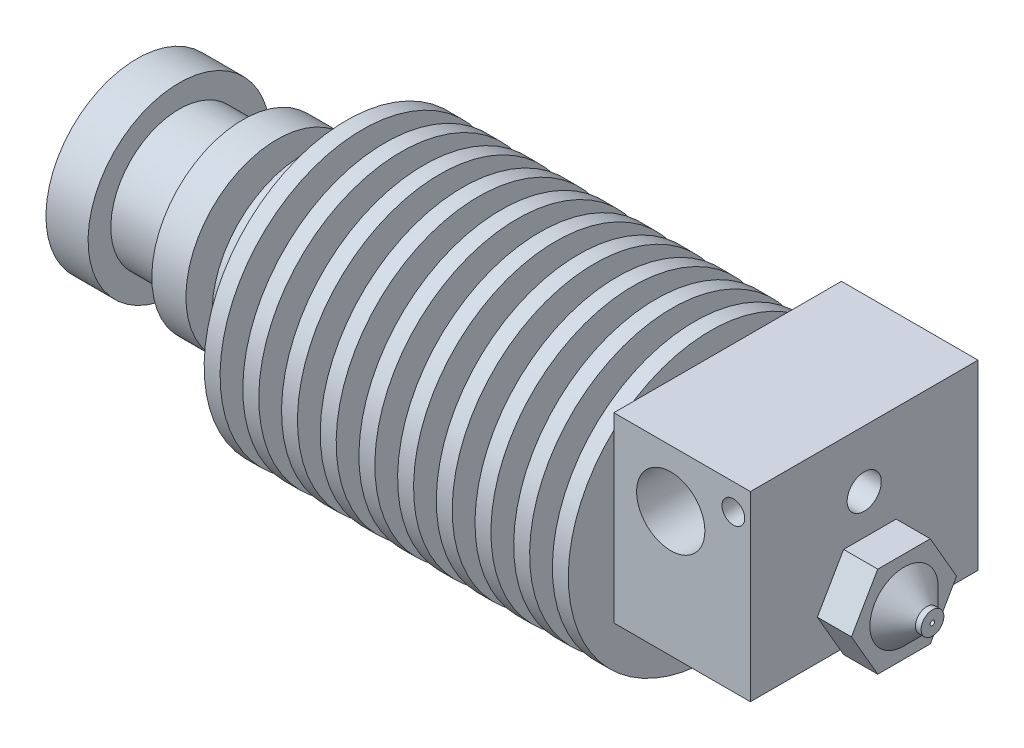
SolidWorks part; units mm, degrees
ref_plane "Front Plane" through (0, 0, 0) normal (0, 0, 1) x (1, 0, 0)
ref_plane "Top Plane" through (0, 0, 0) normal (0, 1, 0) x (1, 0, 0)
ref_plane "Right Plane" through (0, 0, 0) normal (1, 0, 0) x (0, 0, -1)
sketch "Sketch1" plane through (0, 0, 0) normal (0, 0, 1) x (1, 0, 0)
  line L0 (0, 0) -> (69.9, 0) construction
  line L1 (0, -8) -> (0, 8) construction
  line L2 (0, 8) -> (3.7, 8)
  line L3 (3.7, 8) -> (3.7, 6)
  line L4 (3.7, 6) -> (9.3, 6)
  line L5 (9.3, 6) -> (9.3, 8)
  line L6 (9.3, 8) -> (12.3, 8)
  line L7 (12.3, 8) -> (12.3, 3.75)
  line L8 (12.3, 3.75) -> (14.6, 3.75)
  line L9 (14.6, 3.75) -> (14.6, 8)
  line L10 (14.6, 8) -> (16.6, 8)
  line L11 (16.6, 8) -> (16.6, 3.75)
  line L12 (16.6, 3.75) -> (18.4, 3.75)
  line L13 (18.4, 3.75) -> (18.4, 12.5)
  line L14 (18.4, 12.5) -> (50.4, 12.5) construction
  line L15 (50.4, 12.5) -> (50.4, 3)
  line L16 (50.4, 3) -> (64.4, 3)
  line L17 (64.4, 3) -> (64.4, 4)
  line L18 (64.4, 4) -> (67.4, 4)
  line L19 (67.4, 3) -> (69.4, 1)
  line L20 (69.4, 1) -> (69.9, 1)
  line L21 (69.9, 1) -> (69.9, -1) construction
  line L23 (50.4, -12.5) -> (50.4, -3) construction
  line L24 (18.4, -12.5) -> (50.4, -12.5) construction
  line L25 (18.4, -3.75) -> (18.4, -12.5) construction
  line L26 (16.6, -3.75) -> (18.4, -3.75) construction
  line L27 (16.6, -8) -> (16.6, -3.75) construction
  line L28 (14.6, -8) -> (16.6, -8) construction
  line L29 (14.6, -3.75) -> (14.6, -8) construction
  line L30 (12.3, -3.75) -> (14.6, -3.75) construction
  line L31 (12.3, -8) -> (12.3, -3.75) construction
  line L32 (9.3, -8) -> (12.3, -8) construction
  line L33 (9.3, -6) -> (9.3, -8) construction
  line L34 (3.7, -6) -> (9.3, -6) construction
  line L35 (3.7, -8) -> (3.7, -6) construction
  line L36 (0, -8) -> (3.7, -8) construction
  line L37 (69.4, -1) -> (69.9, -1) construction
  line L38 (67.4, -3) -> (69.4, -1) construction
  line L39 (64.4, -4) -> (67.4, -4) construction
  line L40 (64.4, -3) -> (64.4, -4) construction
  line L41 (50.4, -3) -> (64.4, -3) construction
  line L42 (0, 4.75) -> (0, 8)
  line L43 (69.9, 0.2) -> (69.9, 1)
  line L44 (67.4, 3) -> (67.4, -3) construction
  line L45 (67.4, 3) -> (67.4, 4)
  line L46 (67.4, -3) -> (67.4, -4) construction
  line L47 (18.4, 12.5) -> (19.8, 12.5)
  line L48 (19.8, 12.5) -> (19.8, 3.75)
  line L49 (19.8, 3.75) -> (21.8, 3.75)
  line L50 (21.8, 3.75) -> (21.8, 12.5)
  line L51 (21.8, 12.5) -> (23.2, 12.5)
  line L52 (23.2, 12.5) -> (23.2, 3.75)
  line L53 (23.2, 3.75) -> (25.2, 3.75)
  line L54 (25.2, 3.75) -> (25.2, 12.5)
  line L55 (25.2, 12.5) -> (26.6, 12.5)
  line L56 (26.6, 12.5) -> (26.6, 3.75)
  line L57 (26.6, 3.75) -> (28.6, 3.75)
  line L58 (28.6, 3.75) -> (28.6, 12.5)
  line L59 (28.6, 12.5) -> (30, 12.5)
  line L60 (30, 12.5) -> (30, 3.75)
  line L61 (30, 3.75) -> (32, 3.75)
  line L62 (32, 3.75) -> (32, 12.5)
  line L63 (32, 12.5) -> (33.4, 12.5)
  line L64 (33.4, 12.5) -> (33.4, 3.75)
  line L65 (33.4, 3.75) -> (35.4, 3.75)
  line L66 (35.4, 3.75) -> (35.4, 12.5)
  line L67 (35.4, 12.5) -> (36.8, 12.5)
  line L68 (36.8, 12.5) -> (36.8, 3.75)
  line L69 (36.8, 3.75) -> (38.8, 3.75)
  line L70 (38.8, 3.75) -> (38.8, 12.5)
  line L71 (38.8, 12.5) -> (40.2, 12.5)
  line L72 (40.2, 12.5) -> (40.2, 3.75)
  line L73 (40.2, 3.75) -> (42.2, 3.75)
  line L74 (42.2, 3.75) -> (42.2, 12.5)
  line L75 (42.2, 12.5) -> (43.6, 12.5)
  line L76 (43.6, 12.5) -> (43.6, 3.75)
  line L77 (43.6, 3.75) -> (45.6, 3.75)
  line L78 (45.6, 3.75) -> (45.6, 12.5)
  line L79 (45.6, 12.5) -> (47, 12.5)
  line L80 (47, 12.5) -> (47, 3.75)
  line L81 (47, 3.75) -> (49, 3.75)
  line L82 (49, 3.75) -> (49, 12.5)
  line L83 (49, 12.5) -> (50.4, 12.5)
  line L84 (12.3, 3.75) -> (50.4, 3.75) construction
  line L85 (0, 4.75) -> (8, 4.75)
  line L86 (51.9, 12) -> (63.9, 12) construction
  line L87 (51.9, 12) -> (51.9, -4) construction
  line L88 (51.9, -4) -> (63.9, -4) construction
  line L89 (63.9, 12) -> (63.9, -4) construction
  line L90 (8, 4.75) -> (11.75, 1)
  line L91 (11.75, 1) -> (68.6, 1)
  line L92 (68.6, 1) -> (69.4, 0.2)
  line L93 (69.4, 0.2) -> (69.9, 0.2)
  line L94 (8, -4.75) -> (11.75, -1) construction
  line L95 (0, -4.75) -> (8, -4.75) construction
  line L96 (11.75, -1) -> (68.6, -1) construction
  line L97 (69.4, -0.2) -> (69.9, -0.2) construction
  line L98 (68.6, -1) -> (69.4, -0.2) construction
  line L99 (69.4, 1) -> (69.4, -1) construction
  line L100 (8, 4.75) -> (8, -4.75) construction
  dimension "D1" = 8
  dimension "D2" = 2
  dimension "D3" = 6
  dimension "D4" = 16
  dimension "D5" = 12
  dimension "D6" = 3.7
  dimension "D7" = 5.6
  dimension "D8" = 3
  dimension "D9" = 2.3
  dimension "D10" = 2
  dimension "D11" = 1.8
  dimension "D12" = 0.5
  dimension "D13" = 2
  dimension "D14" = 3
  dimension "D15" = 12
  dimension "D16" = 32
  dimension "D17" = 25
  dimension "D18" = 1.4
  dimension "D19" = 2
  dimension "D20" = 16
  dimension "D21" = 0.4
  dimension "D22" = 0.5
  dimension "D23" = 1.5
  dimension "D24" = 7.5
  dimension "D25" = 2
  dimension "D26" = 4
  dimension "D27" = 8
  dimension "D28" = 9.5
ref_axis "Axis1" through (0, 0, 0) along (1, 0, 0)
revolve "Revolve1" add sketch "Sketch1" angle 360 about axis through (0, 0, 0) along (1, 0, 0)
sketch "Sketch2" plane through (64.4, 0, 0) normal (-1, 0, 0) x (0, 0, 1)
  line L0 (0, 0) -> (4, 0) construction
  line L1 (0, 0) -> (-4, 0) construction
  line L2 (2.3094, 4) -> (-2.3094, 4)
  line L3 (-2.3094, 4) -> (-4.6188, 0)
  line L4 (-4.6188, 0) -> (-2.3094, -4)
  line L5 (-2.3094, -4) -> (2.3094, -4)
  line L6 (2.3094, -4) -> (4.6188, 0)
  line L7 (4.6188, 0) -> (2.3094, 4)
  line L8 (0, 0) -> (0, -4) construction
  line L9 (0, 4) -> (0, 0) construction
  line L10 (0, 0) -> (3.4641, 2) construction
  line L11 (0, 0) -> (-3.4641, -2) construction
  circle A1 centre (0, 0) radius 4 construction
  circle A2 centre (0, 0) radius 4 construction
  dimension "D1" = 8
extrude "Boss-Extrude1" add sketch "Sketch2" against normal up to vertex (3 mm away) up to point (67.4, 4, 0)
ref_plane "Plane1" through (63.9, 0, 0) normal (1, 0, 0) x (0, 0, -1)
sketch "Sketch3" plane through (0, 0, 0) normal (0, 0, 1) x (1, 0, 0)
  line L0 (56.9, 7) -> (56.9, 12) construction
  line L1 (51.9, 12) -> (63.9, 12)
  line L2 (51.9, 12) -> (51.9, -4)
  line L3 (51.9, -4) -> (63.9, -4)
  line L4 (63.9, 12) -> (63.9, -4)
  line L5 (56.9, 7) -> (51.9, 7) construction
  line L6 (62.4, 12) -> (62.4, 9.7) construction
  line L7 (62.4, 9.7) -> (63.9, 9.7) construction
  circle A0 centre (56.9, 7) radius 3
  circle A1 centre (62.4, 9.7) radius 1
  dimension "D1" = 6
  dimension "D5" = 2
  dimension "D2" = 5
  dimension "D3" = 1.5
  dimension "D4" = 2.3
sketch "Sketch4" plane through (63.9, 0, 0) normal (1, 0, 0) x (0, 0, -1)
  line L0 (-10, 7) -> (10, 7) construction
  line L1 (-10, 12) -> (10, 12) construction
  line L2 (-10, 12) -> (-10, -4) construction
  line L3 (-10, -4) -> (10, -4) construction
  line L4 (10, 12) -> (10, -4) construction
  line L5 (0, 7) -> (0, 12) construction
  circle A0 centre (0, 7) radius 1.5
  dimension "D2" = 3
  dimension "D1" = 20
extrude "Boss-Extrude2" add sketch "Sketch3" along normal up to vertex (10 mm away) from vertex at -10 starting at point (63.9, 12, -10)
extrude "Cut-Extrude5" cut sketch "Sketch4" against normal up to vertex (12 mm away) up to point (51.9, 12, 0)
sketch "Sketch5" plane through (63.9, 0, 0) normal (1, 0, 0) x (0, 0, -1)
  circle A0 centre (0, 0) radius 1
  circle A1 centre (0, 0) radius 1 construction
extrude "Cut-Extrude6" cut sketch "Sketch5" against normal up to vertex (13.5 mm away) from vertex at 4.7 starting at point (68.6, 1, 0)
